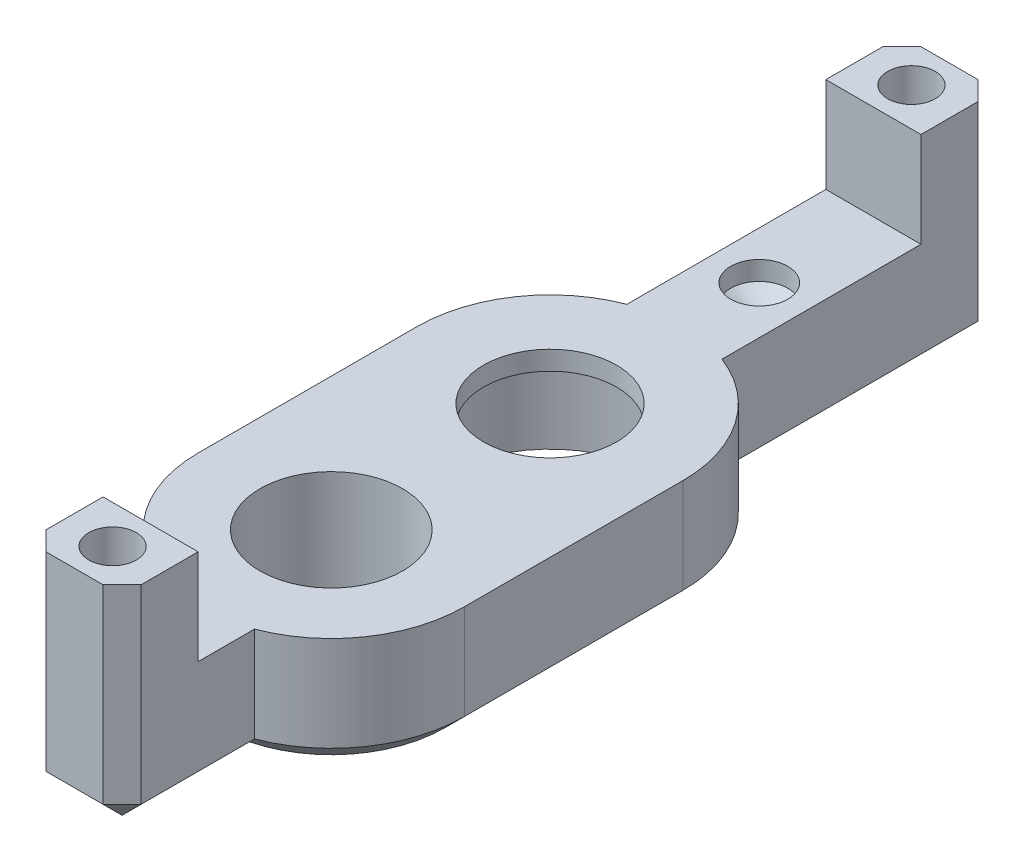
SolidWorks part; units mm, degrees
ref_plane "Plano frontal" through (0, 0, 0) normal (0, 0, 1) x (1, 0, 0)
ref_plane "Plano superior" through (0, 0, 0) normal (0, 1, 0) x (1, 0, 0)
ref_plane "Plano direito" through (0, 0, 0) normal (1, 0, 0) x (0, 0, -1)
sketch "Esboço2" plane through (0, 0, 0) normal (0, 1, 0) x (1, 0, 0)
  line L0 (0, 0) -> (0, 46)
  line L1 (0, 46) -> (14, 46)
  line L2 (14, 46) -> (14, 0)
  line L3 (14, 0) -> (0, 0)
  dimension "D1" = 46
  dimension "D2" = 14
extrude "Ressalto-extrusão1" add sketch "Esboço2" along normal blind 6
sketch "Esboço3" plane through (0, 6, 0) normal (0, 1, 0) x (1, 0, 0)
  line L0 (7, 46) -> (7, 25) construction
  line L1 (14, 46) -> (0, 46) construction
  line L2 (7, 25) -> (7, 13.5) construction
  circle A0 centre (7, 25) radius 4.6
  dimension "D3" = 9.2
  dimension "D1" = 21
  dimension "D2" = 11.5
sketch "Esboço6" plane through (0, 6, 0) normal (0, 1, 0) x (1, 0, 0)
  line L0 (4.5, 46) -> (9.5, 46) construction
  line L1 (14, 46) -> (0, 46) construction
  line L2 (4.5, 46) -> (4.5, 31.5383)
  line L3 (9.5, 46) -> (9.5, 31.5383)
  line L4 (4.5, 46) -> (0, 46)
  line L5 (0, 46) -> (0, 25)
  line L6 (0, 46) -> (0, 0) construction
  line L7 (9.5, 46) -> (14, 46)
  line L8 (14, 46) -> (14, 25)
  line L9 (14, 0) -> (14, 46) construction
  arc A0 (14, 25) -> (9.5, 31.5383) centre (7, 25) ccw
  arc A1 (4.5, 31.5383) -> (0, 25) centre (7, 25) ccw
  point P9 (7, 46)
  dimension "D2" = 5
extrude "Corte-extrusão1" cut sketch "Esboço6" against normal through all
hole_wizard "Furo de diâmetro Ø7.5 (7.5)1" positions "3DSketch2" profile "Esboço8" hole size "Ø7.5" standard "ISO" end condition through all
sketch3d "3DSketch2"
  point P0 (7, 6, -13.5)
sketch "Esboço8" plane through (7, 6, -13.5) normal (1, 0, 0) x (0, 0, 1)
  line L0 (0, 0) -> (0, 6)
  line L1 (0, 6) -> (3.75, 6)
  line L2 (3.75, 6) -> (3.75, 0)
  line L5 (3.75, 0) -> (0, 0)
  line L11 (0, -6.35) -> (0, 107.95) construction
  dimension "Thru Hole Dia." = 7.5
  dimension "Thru Hole Depth" = 6
sketch "Esboço9" plane through (0, 6, 0) normal (0, 1, 0) x (1, 0, 0)
  line L0 (0, 13.5) -> (0, 0)
  line L1 (0, 25) -> (0, 0) construction
  line L2 (0, 0) -> (4.5, 0)
  line L3 (4.5, 0) -> (4.5, 6.9617)
  line L4 (9.5, 0) -> (9.5, 6.9617)
  line L5 (9.5, 0) -> (14, 0)
  line L6 (14, 0) -> (14, 25) construction
  line L7 (14, 0) -> (14, 13.5)
  line L9 (0, 0) -> (14, 0) construction
  arc A0 (0, 13.5) -> (4.5, 6.9617) centre (7, 13.5) ccw
  arc A1 (9.5, 6.9617) -> (14, 13.5) centre (7, 13.5) ccw
  dimension "D1" = 5
extrude "Corte-extrusão2" cut sketch "Esboço9" against normal through all
sketch "Esboço10" plane through (0, 6, 0) normal (0, 1, 0) x (1, 0, 0)
  line L0 (9.5, 46) -> (9.5, 31.5383) construction
  line L1 (4.5, 46) -> (9.5, 46)
  line L2 (4.5, 46) -> (4.5, 42)
  line L3 (4.5, 42) -> (9.5, 42)
  line L4 (9.5, 46) -> (9.5, 42)
  line L5 (9.5, 6.9617) -> (9.5, 0) construction
  line L6 (4.5, 0) -> (9.5, 0)
  line L7 (4.5, 0) -> (4.5, 4)
  line L8 (4.5, 4) -> (9.5, 4)
  line L9 (9.5, 0) -> (9.5, 4)
  dimension "D1" = 4
  dimension "D2" = 4
extrude "Ressalto-extrusão2" add sketch "Esboço10" along normal blind 5
sketch "Esboço11" plane through (0, 11, 0) normal (0, 1, 0) x (1, 0, 0)
  line L0 (7, 46) -> (7, 44) construction
  line L1 (9.5, 46) -> (4.5, 46) construction
  line L2 (7, 46) -> (7, 25) construction
  line L3 (7, 0) -> (7, 2) construction
  line L4 (4.5, 0) -> (9.5, 0) construction
  dimension "D1" = 2
  dimension "D2" = 2
hole_wizard "Broca de rosquear para tarraxa de M31" positions "3DSketch3" profile "Esboço12" hole size "M3" standard "ISO"
sketch3d "3DSketch3"
  point P0 (7, 11, -2)
  point P3 (7, 11, -44)
sketch "Esboço12" plane through (7, 11, -2) normal (1, 0, 0) x (0, 0, 1)
  line L0 (0, 0) -> (0, 4.7511)
  line L1 (0, 4.7511) -> (1.25, 4)
  line L2 (1.25, 4) -> (1.25, 0)
  line L5 (1.25, 0) -> (0, 0)
  line L10 (0, 4.7511) -> (-1.25, 4) construction
  line L11 (0, -6.35) -> (0, 107.95) construction
  dimension "Hole Dia." = 2.5
  dimension "Hole Depth" = 4
  dimension "Drill Angle" = 118
hole_wizard "Furo de diâmetro Ø7.0 (7)1" positions "3DSketch4" profile "Esboço13" hole size "Ø7.0" standard "ISO" end condition through all
sketch3d "3DSketch4"
  point P0 (7, 6, -25)
sketch "Esboço13" plane through (7, 6, -25) normal (1, 0, 0) x (0, 0, 1)
  line L0 (0, 0) -> (0, 6)
  line L1 (0, 6) -> (3.5, 6)
  line L2 (3.5, 6) -> (3.5, 0)
  line L5 (3.5, 0) -> (0, 0)
  line L11 (0, -6.35) -> (0, 107.95) construction
  dimension "Thru Hole Dia." = 7
  dimension "Thru Hole Depth" = 6
sketch "Esboço14" plane through (0, 0, 0) normal (0, -1, 0) x (1, 0, 0)
  circle A0 centre (7, -25) radius 5.55
  dimension "D1" = 11.1
chamfer "Chanfro1" distance 1 angle 45 16 edges at (4.5, 0, -38.7692) (7, 0, -46) (9.5, 0, -38.7692) (4.5, 0, -3.4808) (7, 0, 0) (9.5, 0, -3.4808) (1.2337, 0, -28.9686) (1.2337, 0, -9.5314) (0, 0, -19.25) (12.7663, 0, -9.5314) (12.7663, 0, -28.9686) (14, 0, -19.25) (9.5, 5.5, -46) (4.5, 5.5, -46) (4.5, 5.5, 0) (9.5, 5.5, 0)
sketch "Esboço15" plane through (0, 6, 0) normal (0, 1, 0) x (1, 0, 0)
  line L0 (7, 25) -> (7, 36)
  dimension "D1" = 11
hole_wizard "Furo de diâmetro Ø3.0 (3)1" positions "3DSketch5" profile "Esboço16" hole size "Ø3.0" standard "ISO"
sketch3d "3DSketch5"
  point P0 (7, 6, -36)
sketch "Esboço16" plane through (7, 6, -36) normal (1, 0, 0) x (0, 0, 1)
  line L0 (0, 0) -> (0, 1.9013)
  line L1 (0, 1.9013) -> (1.5, 1)
  line L2 (1.5, 1) -> (1.5, 0)
  line L5 (1.5, 0) -> (0, 0)
  line L10 (0, 1.9013) -> (-1.5, 1) construction
  line L11 (0, -6.35) -> (0, 107.95) construction
  dimension "Hole Dia." = 3
  dimension "Hole Depth" = 1
  dimension "Drill Angle" = 118
sketch "Esboço17" plane through (0, 6, 0) normal (0, 1, 0) x (1, 0, 0)
  circle A0 centre (7, 25) radius 4.55
  dimension "D1" = 9.1
extrude "Corte-extrusão4" cut sketch "Esboço14" against normal blind 5
